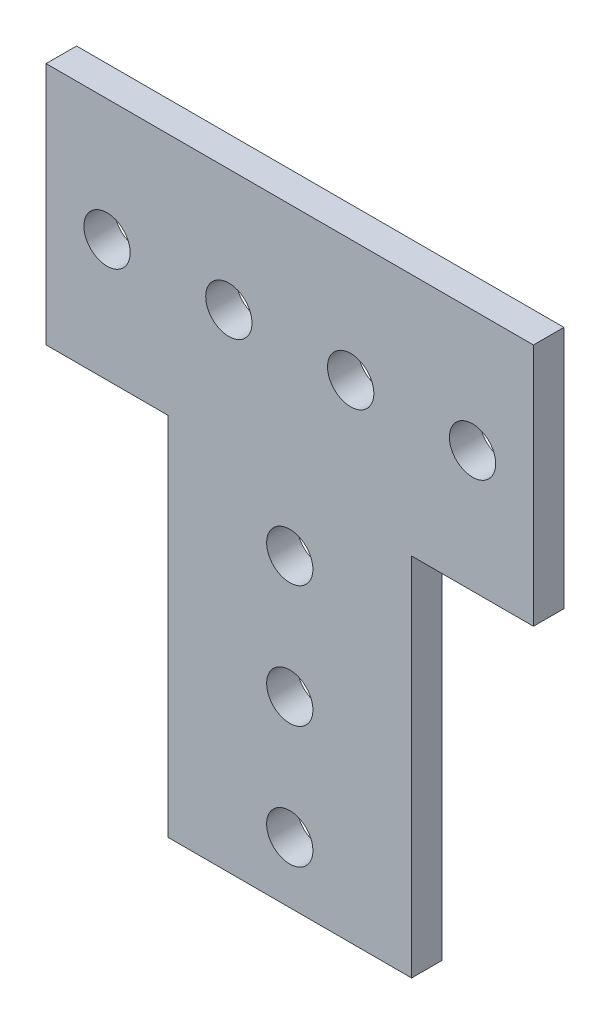
SolidWorks part; units mm, degrees
ref_plane "Front Plane" through (0, 0, 0) normal (0, 0, 1) x (1, 0, 0)
ref_plane "Top Plane" through (0, 0, 0) normal (0, 1, 0) x (1, 0, 0)
ref_plane "Right Plane" through (0, 0, 0) normal (1, 0, 0) x (0, 0, -1)
sketch "Sketch1" plane through (0, 0, 0) normal (0, 0, 1) x (1, 0, 0)
  line L0 (0, 0) -> (0, 38.1)
  line L1 (0, 38.1) -> (-12.7, 38.1)
  line L2 (-12.7, 38.1) -> (-12.7, 63.5)
  line L3 (-12.7, 63.5) -> (38.1, 63.5)
  line L4 (38.1, 63.5) -> (38.1, 38.1)
  line L5 (38.1, 38.1) -> (25.4, 38.1)
  line L6 (25.4, 38.1) -> (25.4, 0)
  line L7 (25.4, 0) -> (0, 0)
  dimension "D1" = 25.4
  dimension "D2" = 25.4
  dimension "D3" = 38.1
  dimension "2" = 38.1
  dimension "D4" = 50.8
  dimension "D5" = 25.4
extrude "Boss-Extrude1" add sketch "Sketch1" along normal blind 3.175
sketch "Sketch2" plane through (0, 0, 0) normal (0, 0, -1) x (-1, 0, 0)
  circle A0 centre (-19.05, 50.8) radius 2.413
  circle A1 centre (-6.35, 50.8) radius 2.413
  circle A2 centre (6.35, 50.8) radius 2.413
  circle A3 centre (-31.75, 50.8) radius 2.413
  dimension "D1" = 4.826
  dimension "D2" = 3
  dimension "D3" = 2
extrude "Cut-Extrude1" cut sketch "Sketch2" against normal through all
sketch "Sketch3" plane through (0, 0, 0) normal (0, 0, -1) x (-1, 0, 0)
  line L0 (0, 38.1) -> (0, 0) construction
  line L1 (12.7, 38.1) -> (0, 38.1) construction
  line L2 (-25.4, 0) -> (-25.4, 38.1) construction
  circle A0 centre (-12.7, 19.05) radius 2.413
  circle A1 centre (-12.7, 31.75) radius 2.413
  circle A2 centre (-12.7, 6.35) radius 2.413
  dimension "D1" = 4.826
  dimension "D2" = 12.7
  dimension "D3" = 19.05
  dimension "D4" = 4.826
  dimension "D5" = 12.7
  dimension "D6" = 6.35
  dimension "D7" = 12.7
  dimension "D8" = 12.7
  dimension "D9" = 4.826
extrude "Cut-Extrude2" cut sketch "Sketch3" against normal through all
